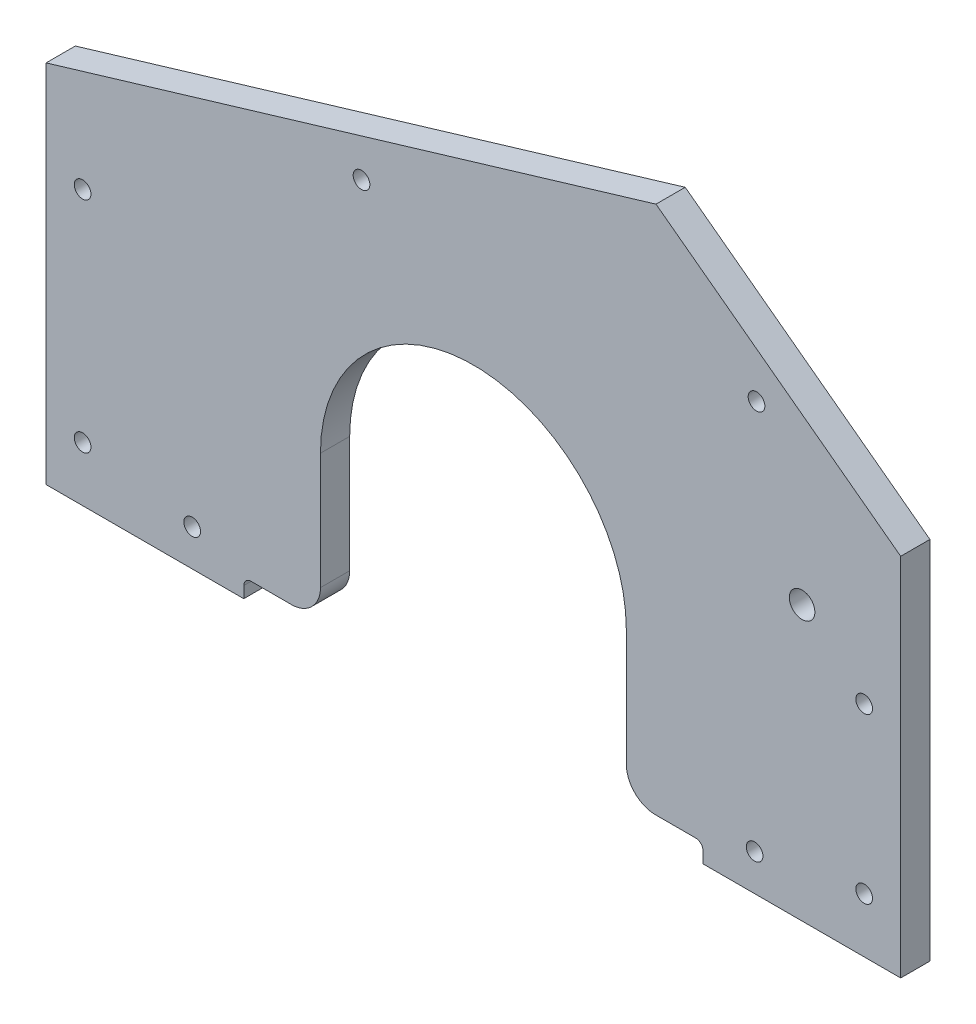
SolidWorks part; units mm, degrees
ref_plane "Front Plane" through (0, 0, 0) normal (0, 0, 1) x (1, 0, 0)
ref_plane "Top Plane" through (0, 0, 0) normal (0, 1, 0) x (1, 0, 0)
ref_plane "Right Plane" through (0, 0, 0) normal (1, 0, 0) x (0, 0, -1)
sketch "Sketch1" plane through (0, 0, 0) normal (0, 0, 1) x (1, 0, 0)
  line L0 (-135.2066, -69.6735) -> (-135.2066, 30.3265)
  line L1 (-135.2066, 30.3265) -> (31.7934, 80.3265)
  line L2 (31.7934, 80.3265) -> (98.7934, 30.3265)
  line L3 (98.7934, 30.3265) -> (98.7934, -69.6735)
  line L4 (98.7934, -69.6735) -> (-135.2066, -69.6735)
  line L5 (31.7934, 80.3265) -> (31.7934, -69.6735) construction
  line L6 (-135.2066, -59.6735) -> (98.7934, -59.6735) construction
  line L7 (-125.2066, 33.3205) -> (-125.2066, -69.6735) construction
  line L8 (-135.2066, 19.8879) -> (41.7761, 72.8768) construction
  line L9 (19.8607, 76.7539) -> (98.7934, 17.8489) construction
  line L10 (88.7934, 37.7892) -> (88.7934, -69.6735) construction
  line L11 (-18.2066, -69.6735) -> (-18.2066, 65.3565) construction
  line L12 (-135.2066, -24.6735) -> (98.7934, -24.6735) construction
  line L13 (-135.2066, 5.3265) -> (98.7934, 5.3265) construction
  line L14 (71.7934, 50.4758) -> (71.7934, -69.6735) construction
  line L15 (65.2934, 55.3265) -> (42.5646, 24.8699) construction
  line L16 (-51.7066, 55.3265) -> (-39.6605, 15.0927) construction
  line L17 (-95.2066, -69.6735) -> (-95.2066, -51.1874) construction
  line L18 (-135.2066, 5.3265) -> (-112.0673, 5.3265) construction
  line L19 (98.7934, -9.6735) -> (76.9523, -9.6735) construction
  circle A0 centre (-125.2066, 5.3265) radius 2.285
  circle A2 centre (-95.2066, -59.6735) radius 2.285
  circle A7 centre (59.3125, 47.3122) radius 2.285
  circle A8 centre (71.7934, 5.3265) radius 7.7375 construction
  circle A9 centre (-48.8384, 45.7467) radius 2.285
  circle A10 centre (58.7934, -59.6735) radius 2.285
  circle A11 centre (-125.2066, -54.6735) radius 2.285
  circle A12 centre (88.7934, -54.6735) radius 2.285
  circle A14 centre (88.7934, -9.6735) radius 2.285
  point P28 (-48.8384, 45.7467)
  point P30 (59.3125, 47.3122)
  point P31 (71.7934, 5.3265)
  point P51 (88.7934, -9.6735)
  point P54 (0, 0)
  dimension "D11" = 4.57
  dimension "D12" = 15
  dimension "D13" = 4.57
  dimension "D14" = 25
  dimension "D15" = 4.57
  dimension "D16" = 4.57
  dimension "D18" = 4.57
  dimension "D22" = 15.475
  dimension "D1" = 234
  dimension "D2" = 100
  dimension "D3" = 100
  dimension "D4" = 50
  dimension "D5" = 67
  dimension "D6" = 10
  dimension "D7" = 10
  dimension "D8" = 10
  dimension "D9" = 10
  dimension "D10" = 10
  dimension "D19" = 45
  dimension "D20" = 30
  dimension "D21" = 90
  dimension "D23" = 40
extrude "Boss-Extrude1" add sketch "Sketch1" against normal blind 8
sketch "Sketch2" plane through (0, 0, 0) normal (0, 0, 1) x (1, 0, 0)
  line L0 (-135.2066, 5.3265) -> (98.7934, 5.3265) construction
  line L1 (71.7934, 50.4758) -> (71.7934, -69.6735) construction
  line L2 (-135.2066, 5.3265) -> (98.7934, 5.3265) construction
  line L3 (71.7934, 50.4758) -> (71.7934, -69.6735) construction
  circle A0 centre (71.7934, 5.3265) radius 7.7375 construction
  circle A1 centre (71.7934, 5.3265) radius 7.7375 construction
  circle A2 centre (71.7934, 5.3265) radius 15
  dimension "D1" = 30
extrude "Boss-Extrude2" add sketch "Sketch2" against normal blind 15
sketch "Sketch3" plane through (0, 0, 0) normal (0, 0, 1) x (1, 0, 0)
  line L0 (98.7934, -69.6735) -> (-135.2066, -69.6735) construction
  line L1 (-135.2066, -24.6735) -> (98.7934, -24.6735) construction
  line L2 (-18.2066, -69.6735) -> (-18.2066, 65.3565) construction
  line L3 (98.7934, -69.6735) -> (-135.2066, -69.6735) construction
  line L4 (-135.2066, -24.6735) -> (98.7934, -24.6735) construction
  line L5 (-18.2066, -69.6735) -> (-18.2066, 65.3565) construction
  line L6 (23.6684, -24.6735) -> (23.6684, -69.6735) construction
  line L7 (-60.0816, -24.6735) -> (-60.0816, -69.6735) construction
  line L8 (-81.0816, -66.5485) -> (44.6684, -66.5485) construction
  line L9 (-81.0816, -69.6735) -> (-81.0816, -66.5485) construction
  line L10 (44.6684, -69.6735) -> (44.6684, -66.5485) construction
  line L11 (-81.0816, -64.5435) -> (44.6684, -64.5435) construction
  line L13 (44.6684, -69.6735) -> (44.6684, -64.5435)
  line L14 (44.6684, -64.5435) -> (23.6684, -64.5435)
  line L15 (23.6684, -64.5435) -> (23.6684, -24.6735)
  line L16 (-81.0816, -69.6735) -> (-81.0816, -64.5435)
  line L17 (-81.0816, -64.5435) -> (-60.0816, -64.5435)
  line L18 (-60.0816, -64.5435) -> (-60.0816, -24.6735)
  line L19 (-81.0816, -69.6735) -> (-81.0816, -72.3335)
  line L20 (-81.0816, -72.3335) -> (44.6684, -72.3335)
  line L21 (44.6684, -72.3335) -> (44.6684, -69.6735)
  line L22 (-135.2066, 5.3265) -> (98.7934, 5.3265) construction
  line L23 (71.7934, 50.4758) -> (71.7934, -69.6735) construction
  line L24 (-135.2066, 5.3265) -> (98.7934, 5.3265) construction
  line L25 (71.7934, 50.4758) -> (71.7934, -69.6735) construction
  circle A0 centre (-18.2066, -24.6735) radius 41.875 construction
  arc A1 (-60.0816, -24.6735) -> (23.6684, -24.6735) centre (-18.2066, -24.6735) cw
  circle A2 centre (71.7934, 5.3265) radius 3.5
  point P16 (-18.2066, -66.5485)
  dimension "D1" = 83.75
  dimension "D5" = 7
  dimension "D2" = 62.875
  dimension "D3" = 5.13
  dimension "D4" = 2.66
extrude "Cut-Extrude1" cut sketch "Sketch3" against normal blind 18 and the other way blind 2
sketch "Sketch4" plane through (0, 0, 0) normal (0, 0, 1) x (1, 0, 0)
  line L0 (-135.2066, 5.3265) -> (98.7934, 5.3265) construction
  line L1 (71.7934, 50.4758) -> (71.7934, -69.6735) construction
  line L2 (-135.2066, 5.3265) -> (98.7934, 5.3265) construction
  line L3 (71.7934, 50.4758) -> (71.7934, -69.6735) construction
  circle A0 centre (71.7934, 5.3265) radius 7.7375 construction
  circle A1 centre (71.7934, 5.3265) radius 7.7375
extrude "Cut-Extrude2" cut sketch "Sketch4" against normal blind 6 from offset 10.222 offset against normal yes
fillet "Fillet1" radius 8 2 edges at (-60.0816, -64.5435, -4) (23.6684, -64.5435, -4)
fillet "Fillet2" radius 2 2 edges at (-81.0816, -64.5435, -4) (44.6684, -64.5435, -4)
chamfer "Chamfer1" distance 2 angle 45 1 edges at (56.7934, 5.3265, -8)
